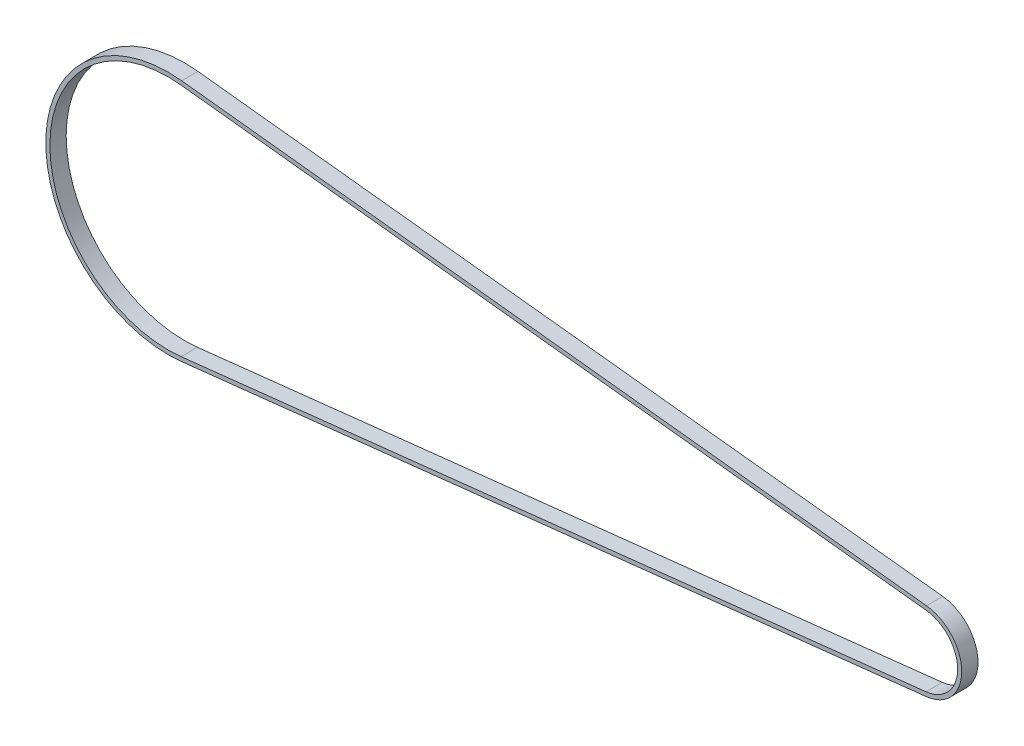
SolidWorks part; units mm, degrees
material "Natural Rubber"
ref_plane "Front" through (0, 0, 0) normal (0, 0, 1) x (1, 0, 0)
ref_plane "Top" through (0, 0, 0) normal (0, 1, 0) x (1, 0, 0)
ref_plane "Right" through (0, 0, 0) normal (1, 0, 0) x (0, 0, -1)
sketch "Sketch1" plane through (0, 0, 0) normal (0, 0, 1) x (1, 0, 0)
  line L0 (15.1903, 137.594) -> (886.936, 41.354)
  line L1 (886.936, -41.354) -> (15.1903, -137.594)
  arc A0 (15.1903, 137.594) -> (15.1903, -137.594) centre (0, 0) ccw
  arc A1 (886.936, -41.354) -> (886.936, 41.354) centre (882.3706, 0) ccw
  dimension "D2" = 276.86
  dimension "D3" = 83.2104
  dimension "D1" = 882.3706
extrude "Extrude-Thin1" add sketch "Sketch1" along normal blind 19.05 thin thin type one direction wall 4.7625
